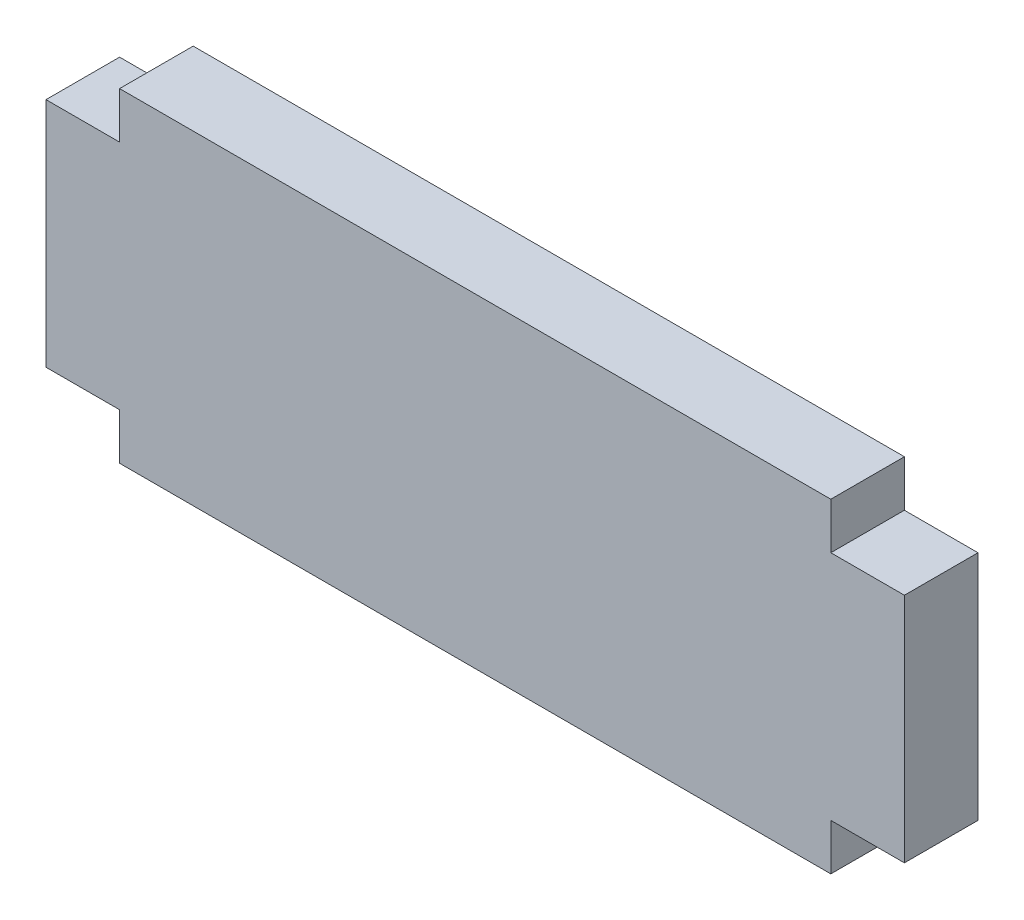
SolidWorks part; units mm, degrees
ref_plane "Front Plane" through (0, 0, 0) normal (0, 0, 1) x (1, 0, 0)
ref_plane "Top Plane" through (0, 0, 0) normal (0, 1, 0) x (1, 0, 0)
ref_plane "Right Plane" through (0, 0, 0) normal (1, 0, 0) x (0, 0, -1)
sketch "Sketch2" plane through (0, 0, 0) normal (0, 0, 1) x (1, 0, 0)
  line L1 (-15.3423, -7) -> (15.3423, -7)
  line L2 (-15.3423, -7) -> (-15.3423, 7)
  line L3 (-15.3423, 7) -> (15.3423, 7)
  line L4 (15.3423, -7) -> (15.3423, 7)
  line L5 (-15.3423, -7) -> (15.3423, 7) construction
  line L6 (-15.3423, 7) -> (15.3423, -7) construction
  line L7 (-15.3423, 5) -> (-18.5173, 5)
  line L8 (-15.3423, 5) -> (-15.3423, -5)
  line L9 (-15.3423, -5) -> (-18.5173, -5)
  line L10 (-18.5173, 5) -> (-18.5173, -5)
  line L11 (15.3423, 5) -> (18.5173, 5)
  line L12 (15.3423, 5) -> (15.3423, -5)
  line L13 (15.3423, -5) -> (18.5173, -5)
  line L14 (18.5173, 5) -> (18.5173, -5)
  point P0 (0, 0)
  dimension "D1" = 3.175
  dimension "D2" = 3.175
  dimension "D3" = 10
  dimension "D4" = 14
  dimension "D5" = 10
  dimension "D6" = 2
  dimension "D7" = 2
  dimension "D8" = 30.6846
extrude "Boss-Extrude1" add sketch "Sketch2" along normal blind 3.175 contours L7 L10 L9 L2 | L1 L4 L3 L2 | L14 L11 L4 L13
